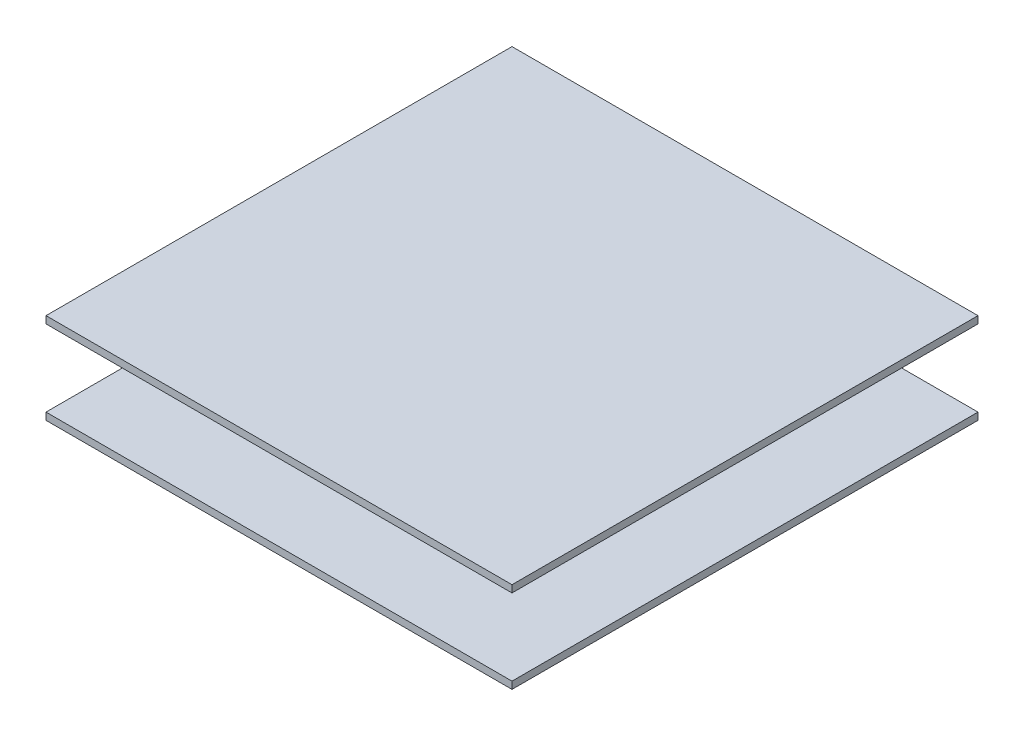
SolidWorks part; units mm, degrees
ref_plane "Front Plane" through (0, 0, 0) normal (0, 0, 1) x (1, 0, 0)
ref_plane "Top Plane" through (0, 0, 0) normal (0, 1, 0) x (1, 0, 0)
ref_plane "Right Plane" through (0, 0, 0) normal (1, 0, 0) x (0, 0, -1)
sketch "Sketch1" plane through (0, 0, 0) normal (0, 0, 1) x (1, 0, 0)
  line L1 (0, 0) -> (12.7, 0)
  line L2 (0, 0) -> (0, 12.7)
  line L3 (0, 12.7) -> (12.7, 12.7)
  line L4 (12.7, 0) -> (12.7, 12.7)
  dimension "D1" = 12.7
extrude "Boss-Extrude1" add sketch "Sketch1" along normal blind 80
sketch "Sketch2" plane through (0, 12.7, 0) normal (0, 1, 0) x (1, 0, 0)
  line L0 (12.7, 0) -> (0, 0) construction
  circle A0 centre (6.6687, -5) radius 2
  circle A1 centre (6.6687, -20) radius 2
  circle A2 centre (6.6687, -60) radius 2
  circle A3 centre (6.6687, -75) radius 2
  dimension "D1" = 4
  dimension "D2" = 5
  dimension "D3" = 15
  dimension "D4" = 40
  dimension "D5" = 15
extrude "Cut-Extrude1" cut sketch "Sketch2" against normal through all
sketch "Sketch4" plane through (0, 0, 0) normal (-1, 0, 0) x (0, 0, 1)
  line L0 (40, 0) -> (40, 12.7) construction
  line L1 (80, 0) -> (0, 0) construction
  line L2 (80, 12.7) -> (0, 12.7) construction
  line L3 (-1.1232, 205.6227) -> (294.8768, 205.6227) construction
  arc A0 (40, 2.7275) -> (40, 9.9725) centre (43.8, 6.35) ccw
  arc A1 (40, 9.9725) -> (40, 2.7275) centre (36.2, 6.35) ccw
  point P13 (40, 6.35)
  dimension "D1" = 10.5
  dimension "D3" = 10.5
  dimension "D4" = 3.8
extrude "Cut-Extrude2" cut sketch "Sketch4" against normal through all
sketch "Sketch5" plane through (0, 0, 0) normal (0, 1, 0) x (1, 0, 0)
  circle A0 centre (6.6687, -20) radius 2 construction
  circle A1 centre (6.6687, -5) radius 2 construction
  circle A2 centre (6.6687, -20) radius 2
  circle A3 centre (6.6687, -5) radius 2
extrude "Boss-Extrude2" add sketch "Sketch5" along normal blind 17
sketch "Sketch6" plane through (0, 12.7, 0) normal (0, 1, 0) x (1, 0, 0)
  circle A0 centre (6.6687, -75) radius 2 construction
  circle A1 centre (6.6687, -60) radius 2 construction
  circle A2 centre (6.6687, -75) radius 2
  circle A3 centre (6.6687, -60) radius 2
extrude "Boss-Extrude3" add sketch "Sketch6" against normal blind 17
sketch "Sketch7" plane through (0, 17, 0) normal (0, 1, 0) x (1, 0, 0)
  line L0 (12.7, 0) -> (0, 0) construction
  line L1 (-58.65, -105) -> (71.35, -105)
  line L2 (-58.65, -105) -> (-58.65, 25)
  line L3 (-58.65, 25) -> (71.35, 25)
  line L4 (71.35, -105) -> (71.35, 25)
  line L6 (0, -80) -> (0, 0) construction
  dimension "D1" = 130
  dimension "D2" = 130
  dimension "D3" = 25
  dimension "D4" = 58.65
extrude "Boss-Extrude4" add sketch "Sketch7" along normal blind 2
sketch "Sketch8" plane through (0, -4.3, 0) normal (0, -1, 0) x (1, 0, 0)
  line L16 (-58.65, 105) -> (-58.65, -25)
  line L17 (-58.65, -25) -> (71.35, -25)
  line L18 (71.35, -25) -> (71.35, 105)
  line L19 (71.35, 105) -> (-58.65, 105)
  line L20 (-58.65, 105) -> (-58.65, -25)
  line L21 (-58.65, -25) -> (71.35, -25)
  line L22 (71.35, -25) -> (71.35, 105)
  line L23 (71.35, 105) -> (-58.65, 105)
  dimension "D1" = 0
extrude "Boss-Extrude5" add sketch "Sketch8" along normal blind 2
